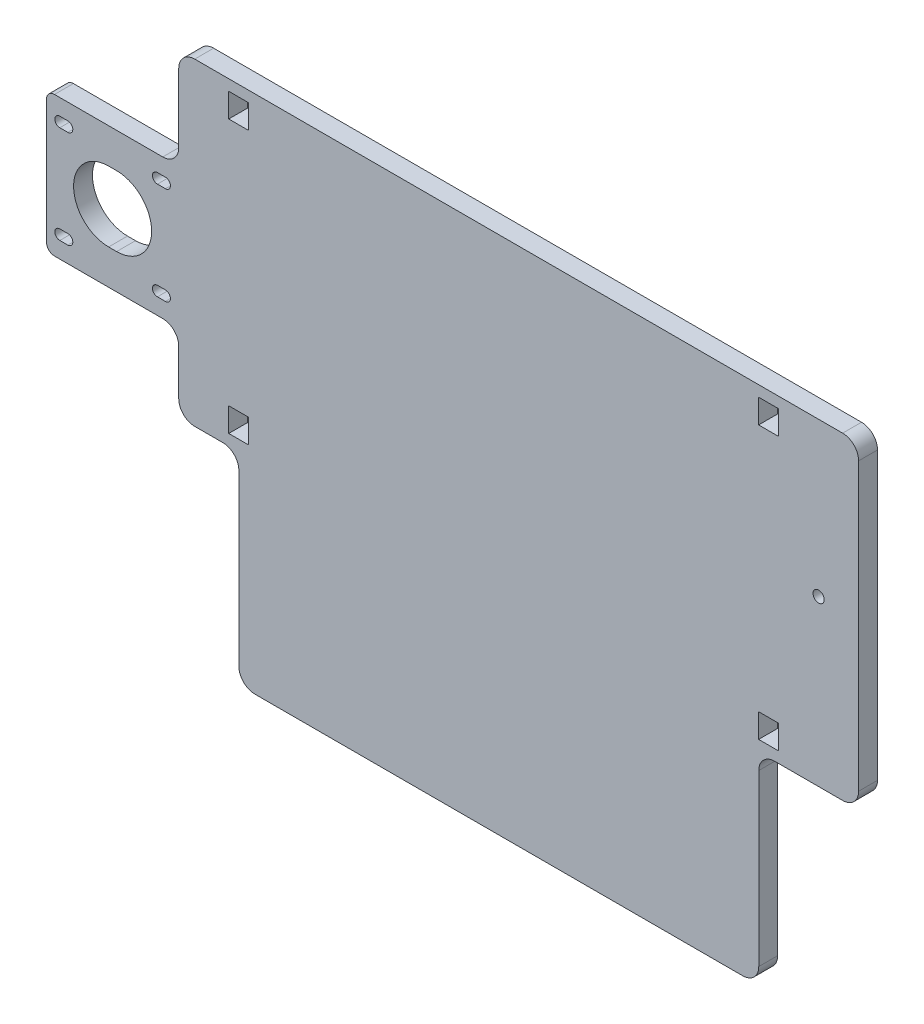
SolidWorks part; units mm, degrees
material "Acrylic (Medium-high impact)"
ref_plane "Front Plane" through (0, 0, 0) normal (0, 0, 1) x (1, 0, 0)
ref_plane "Top Plane" through (0, 0, 0) normal (0, 1, 0) x (1, 0, 0)
ref_plane "Right Plane" through (0, 0, 0) normal (1, 0, 0) x (0, 0, -1)
sketch "Sketch1" plane through (0, 0, 0) normal (0, 0, 1) x (1, 0, 0)
  line L1 (0, 0) -> (257.9, 0)
  line L2 (0, 0) -> (0, 165.1)
  line L3 (0, 165.1) -> (257.9, 165.1)
  line L4 (257.9, 0) -> (257.9, 165.1)
  line L5 (232.5, 161.6456) -> (226.15, 161.6456)
  line L6 (232.5, 161.6456) -> (232.5, 154.0256)
  line L7 (232.5, 154.0256) -> (226.15, 154.0256)
  line L8 (226.15, 161.6456) -> (226.15, 154.0256)
  line L9 (57.875, 161.6456) -> (64.225, 161.6456)
  line L10 (57.875, 161.6456) -> (57.875, 154.0256)
  line L11 (57.875, 154.0256) -> (64.225, 154.0256)
  line L12 (64.225, 161.6456) -> (64.225, 154.0256)
  line L13 (232.5, 67.5386) -> (226.15, 67.5386)
  line L14 (232.5, 67.5386) -> (232.5, 75.1586)
  line L15 (232.5, 75.1586) -> (226.15, 75.1586)
  line L16 (226.15, 67.5386) -> (226.15, 75.1586)
  line L17 (64.225, 67.5386) -> (57.875, 67.5386)
  line L18 (64.225, 67.5386) -> (64.225, 75.1586)
  line L19 (64.225, 75.1586) -> (57.875, 75.1586)
  line L20 (57.875, 67.5386) -> (57.875, 75.1586)
  dimension "D1" = 257.9
  dimension "D2" = 165.1
  dimension "D3" = 7.62
  dimension "D4" = 6.35
  dimension "D5" = 25.4
  dimension "D6" = 174.625
  dimension "D7" = 3.4544
  dimension "D8" = 78.867
extrude "Boss-Extrude1" add sketch "Sketch1" along normal blind 6
ref_plane "Plane1" through (0, 114.5921, 0) normal (0, -1, 0) x (1, 0, 0)
sketch "Sketch2" plane through (0, 0, 6) normal (0, 0, 1) x (1, 0, 0)
  line L0 (0, 114.5921) -> (257.9, 114.5921) construction
  line L1 (0, 165.1) -> (0, 0) construction
  line L2 (257.9, 0) -> (257.9, 165.1) construction
  line L3 (-3.3, 114.5921) -> (3.3, 114.5921) construction
  line L4 (0, 104.6353) -> (257.9, 104.6353) construction
  line L5 (4.23, 126.3837) -> (6.77, 126.3837) construction
  line L6 (5.5, 126.3837) -> (36.5, 126.3837) construction
  line L7 (5.5, 126.3837) -> (5.5, 95.3837) construction
  line L8 (5.5, 95.3837) -> (36.5, 95.3837) construction
  line L9 (36.5, 126.3837) -> (36.5, 95.3837) construction
  line L10 (5.5, 126.3837) -> (36.5, 95.3837) construction
  line L11 (5.5, 95.3837) -> (36.5, 126.3837) construction
  line L12 (4.23, 127.9712) -> (6.77, 127.9712)
  line L13 (4.23, 124.7962) -> (6.77, 124.7962)
  line L14 (35.23, 126.3837) -> (37.77, 126.3837) construction
  line L15 (35.23, 127.9712) -> (37.77, 127.9712)
  line L16 (35.23, 124.7962) -> (37.77, 124.7962)
  line L17 (35.23, 95.3837) -> (37.77, 95.3837) construction
  line L18 (35.23, 96.9712) -> (37.77, 96.9712)
  line L19 (35.23, 93.7962) -> (37.77, 93.7962)
  line L20 (4.23, 95.3837) -> (6.77, 95.3837) construction
  line L21 (4.23, 96.9712) -> (6.77, 96.9712)
  line L22 (4.23, 93.7962) -> (6.77, 93.7962)
  line L23 (19.73, 110.8837) -> (22.27, 110.8837) construction
  line L24 (19.73, 122.0087) -> (22.27, 122.0087)
  line L25 (19.73, 99.7587) -> (22.27, 99.7587)
  circle A0 centre (245.2, 116.3447) radius 1.778
  circle A1 centre (5.5, 126.3837) radius 1.5875 construction
  circle A2 centre (36.5, 126.3837) radius 1.5875 construction
  circle A3 centre (36.5, 95.3837) radius 1.5875 construction
  circle A4 centre (5.5, 95.3837) radius 1.5875 construction
  circle A5 centre (21, 110.8837) radius 11.125 construction
  arc A6 (4.23, 127.9712) -> (4.23, 124.7962) centre (4.23, 126.3837) ccw
  arc A7 (6.77, 124.7962) -> (6.77, 127.9712) centre (6.77, 126.3837) ccw
  arc A8 (35.23, 127.9712) -> (35.23, 124.7962) centre (35.23, 126.3837) ccw
  arc A9 (37.77, 124.7962) -> (37.77, 127.9712) centre (37.77, 126.3837) ccw
  arc A10 (35.23, 96.9712) -> (35.23, 93.7962) centre (35.23, 95.3837) ccw
  arc A11 (37.77, 93.7962) -> (37.77, 96.9712) centre (37.77, 95.3837) ccw
  arc A12 (4.23, 96.9712) -> (4.23, 93.7962) centre (4.23, 95.3837) ccw
  arc A13 (6.77, 93.7962) -> (6.77, 96.9712) centre (6.77, 95.3837) ccw
  arc A14 (19.73, 122.0087) -> (19.73, 99.7587) centre (19.73, 110.8837) ccw
  arc A15 (22.27, 99.7587) -> (22.27, 122.0087) centre (22.27, 110.8837) ccw
  point P12 (21, 110.8837)
  point P25 (5.5, 126.3837)
  point P30 (36.5, 126.3837)
  point P39 (36.5, 95.3837)
  point P44 (5.5, 95.3837)
  point P53 (21, 110.8837)
  dimension "D4" = 3.556
  dimension "D7" = 3.175
  dimension "D8" = 22.25
  dimension "D1" = 9.9568
  dimension "D2" = 1.7526
  dimension "D3" = 12.7
  dimension "D5" = 6.2484
  dimension "D6" = 31
  dimension "D9" = 21
  dimension "D10" = 2.54
  dimension "D11" = 2.54
extrude "Cut-Extrude1" cut sketch "Sketch2" against normal through all
sketch "Sketch3" plane through (0, 0, 6) normal (0, 0, 1) x (1, 0, 0)
  line L0 (61.087, 0) -> (61.087, 64.0842)
  line L1 (0, 0) -> (257.9, 0) construction
  line L2 (61.087, 64.0842) -> (42, 64.0842)
  line L3 (42, 64.0842) -> (42, 88.6587)
  line L4 (42, 88.6587) -> (0, 88.6587)
  line L5 (0, 165.1) -> (0, 0) construction
  line L6 (0, 88.6587) -> (0, 0)
  line L7 (0, 0) -> (61.087, 0)
  line L8 (42, 165.1) -> (42, 133.1087)
  line L9 (257.9, 165.1) -> (0, 165.1) construction
  line L10 (42, 133.1087) -> (0, 133.1087)
  line L11 (0, 133.1087) -> (0, 165.1)
  line L12 (0, 165.1) -> (42, 165.1)
  line L13 (257.9, 0) -> (257.9, 64.0842)
  line L14 (257.9, 0) -> (257.9, 165.1) construction
  line L15 (257.9, 64.0842) -> (226.187, 64.0842)
  line L16 (226.187, 64.0842) -> (226.187, 0)
  line L17 (226.187, 0) -> (257.9, 0)
  line L18 (21, 110.8837) -> (21, 133.1087) construction
  line L19 (21, 110.8837) -> (21, 88.6587) construction
  line L20 (21, 110.8837) -> (8.605, 110.8837) construction
  arc A0 (19.73, 122.0087) -> (19.73, 99.7587) centre (19.73, 110.8837) ccw construction
  dimension "D1" = 61.087
  dimension "D2" = 215.9
  dimension "D3" = 165.1
  dimension "D4" = 44.45
  dimension "D5" = 3.4544
extrude "Cut-Extrude2" cut sketch "Sketch3" against normal through all
fillet "Fillet1" radius 5.08 10 edges at (42, 133.1087, 3) (42, 88.6587, 3) (61.087, 64.0842, 3) (226.187, 64.0842, 3) (257.9, 64.0842, 3) (226.187, 0, 3) (61.087, 0, 3) (42, 64.0842, 3) (257.9, 165.1, 3) (42, 165.1, 3)
fillet "Fillet2" radius 2.54 2 edges at (0, 88.6587, 3) (0, 133.1087, 3)
